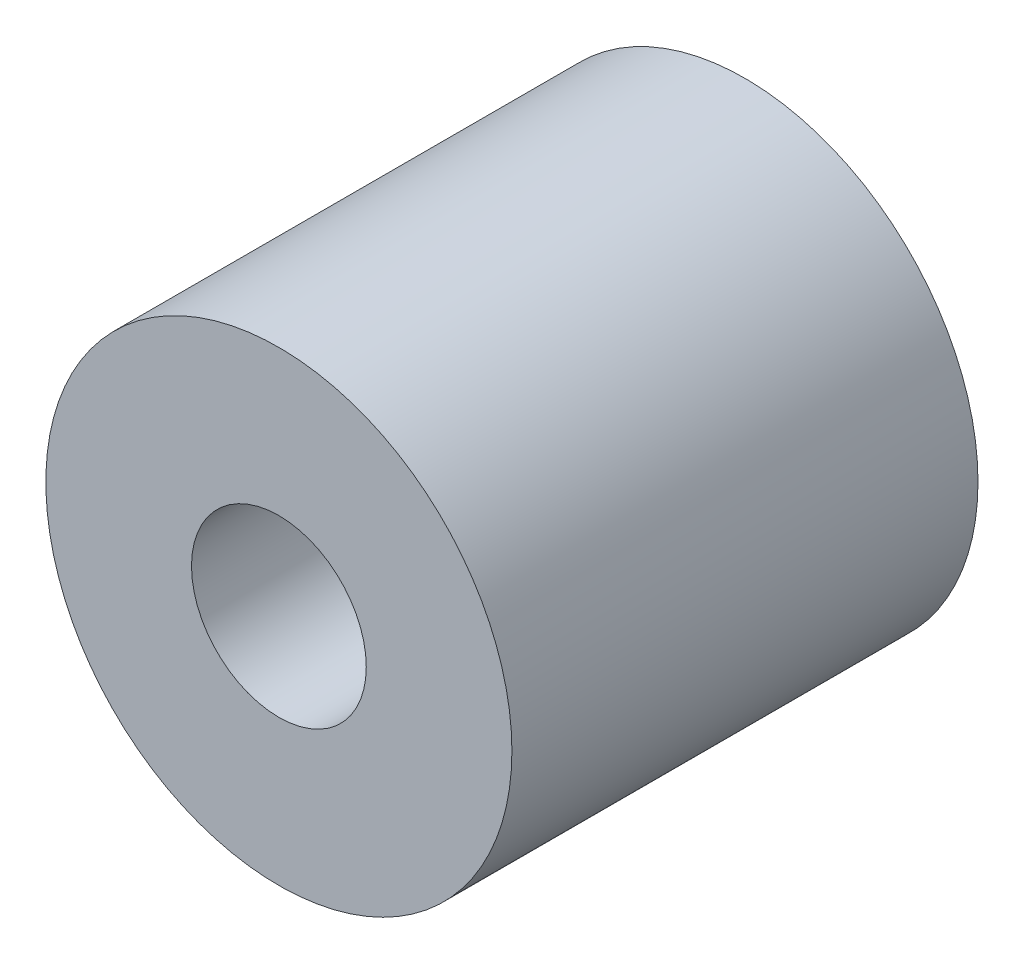
SolidWorks part; units mm, degrees
ref_plane "Front Plane" through (0, 0, 0) normal (0, 0, 1) x (1, 0, 0)
ref_plane "Top Plane" through (0, 0, 0) normal (0, 1, 0) x (1, 0, 0)
ref_plane "Right Plane" through (0, 0, 0) normal (1, 0, 0) x (0, 0, -1)
sketch "Sketch1" plane through (0, 0, 0) normal (0, 0, 1) x (1, 0, 0)
  circle A0 centre (0, 0) radius 4
  circle A1 centre (0, 0) radius 3.075
  dimension "D1" = 8
  dimension "D2" = 6.15
extrude "Boss-Extrude1" add sketch "Sketch1" along normal blind 8
sketch "Sketch2" plane through (0, 0, 8) normal (0, 0, 1) x (1, 0, 0)
  circle A0 centre (0, 0) radius 3.075
  circle A1 centre (0, 0) radius 1.5
  dimension "D1" = 3
  dimension "D2" = 6.15
extrude "Boss-Extrude2" add sketch "Sketch2" against normal offset from surface (5.5 mm away) 2.5 up to face at (4, 0, 0)
chamfer "Chamfer1" distance 0.2 angle 45 1 edges at (3.075, 0, 0)
